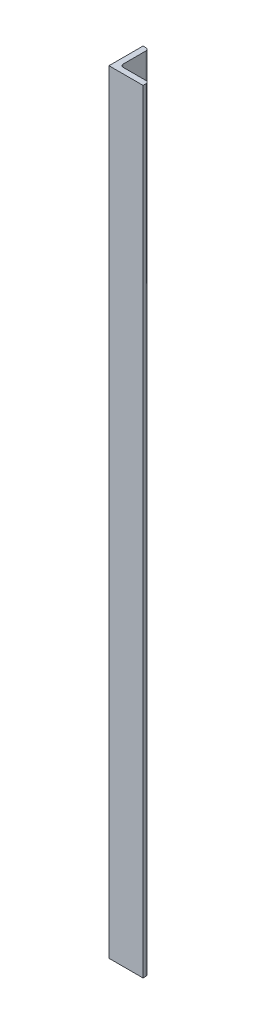
SolidWorks part; units mm, degrees
material "6061 Alloy"
ref_plane "Front Plane" through (0, 0, 0) normal (0, 0, 1) x (1, 0, 0)
ref_plane "Top Plane" through (0, 0, 0) normal (0, 1, 0) x (1, 0, 0)
ref_plane "Right Plane" through (0, 0, 0) normal (1, 0, 0) x (0, 0, -1)
sketch "Sketch2" plane through (0, 0, 0) normal (0, 1, 0) x (1, 0, 0)
  line L0 (0, 0) -> (19.05, 0)
  line L1 (0, 0) -> (0, 19.05)
  line L2 (4.7625, 3.175) -> (17.4625, 3.175)
  line L3 (3.175, 4.7625) -> (3.175, 17.4625)
  line L4 (0, 19.05) -> (1.5875, 19.05)
  line L5 (19.05, 1.5875) -> (19.05, 0)
  line L6 (3.175, 3.175) -> (3.175, 19.05) construction
  line L7 (3.175, 3.175) -> (19.05, 3.175) construction
  arc A0 (3.175, 17.4625) -> (1.5875, 19.05) centre (1.5875, 17.4625) ccw
  arc A1 (3.175, 4.7625) -> (4.7625, 3.175) centre (4.7625, 4.7625) ccw
  arc A2 (17.4625, 3.175) -> (19.05, 1.5875) centre (17.4625, 1.5875) cw
  dimension "D2" = 1.5875
  dimension "D1" = 3.175
extrude "Boss-Extrude1" add sketch "Sketch2" along normal blind 431.8
sketch "Sketch3" plane through (0, 0, -3.175) normal (0, 0, -1) x (-1, 0, 0)
  line L0 (-19.05, 0) -> (-3.175, 0) construction
  line L1 (-11.1125, 0) -> (-11.1125, 15.875) construction
  circle A0 centre (-11.1125, 7.9375) radius 1.688
